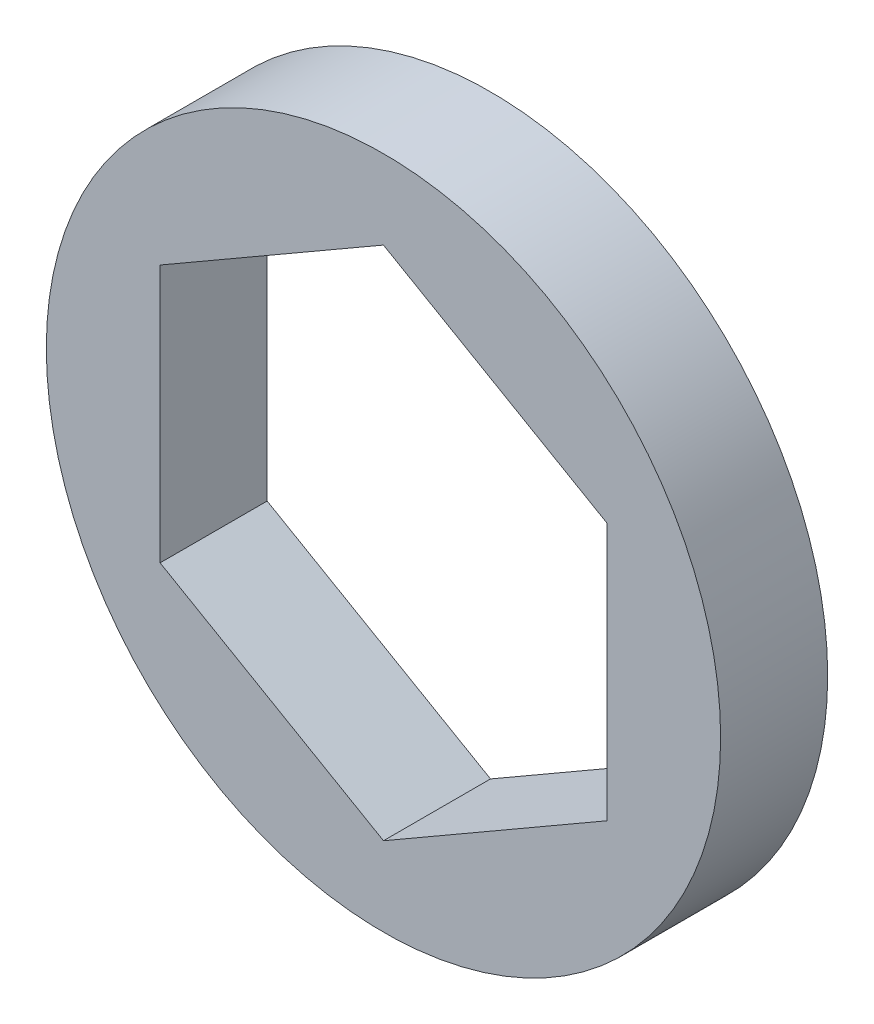
SolidWorks part; units mm, degrees
material "Nylon 101"
ref_plane "Front Plane" through (0, 0, 0) normal (0, 0, 1) x (1, 0, 0)
ref_plane "Top Plane" through (0, 0, 0) normal (0, 1, 0) x (1, 0, 0)
ref_plane "Right Plane" through (0, 0, 0) normal (1, 0, 0) x (0, 0, -1)
sketch "Sketch1" plane through (0, 0, 0) normal (0, 0, 1) x (1, 0, 0)
  line L1 (0, 7.7723) -> (-6.731, 3.8861)
  line L2 (-6.731, 3.8861) -> (-6.731, -3.8861)
  line L3 (-6.731, -3.8861) -> (0, -7.7723)
  line L4 (0, -7.7723) -> (6.731, -3.8861)
  line L5 (6.731, -3.8861) -> (6.731, 3.8861)
  line L6 (6.731, 3.8861) -> (0, 7.7723)
  circle A0 centre (0, 0) radius 10.16
  circle A1 centre (0, 0) radius 6.731 construction
  point P3 (0, 0)
  dimension "D1" = 20.32
  dimension "D2" = 13.462
extrude "Boss-Extrude1" add sketch "Sketch1" along normal mid plane 3.2258
